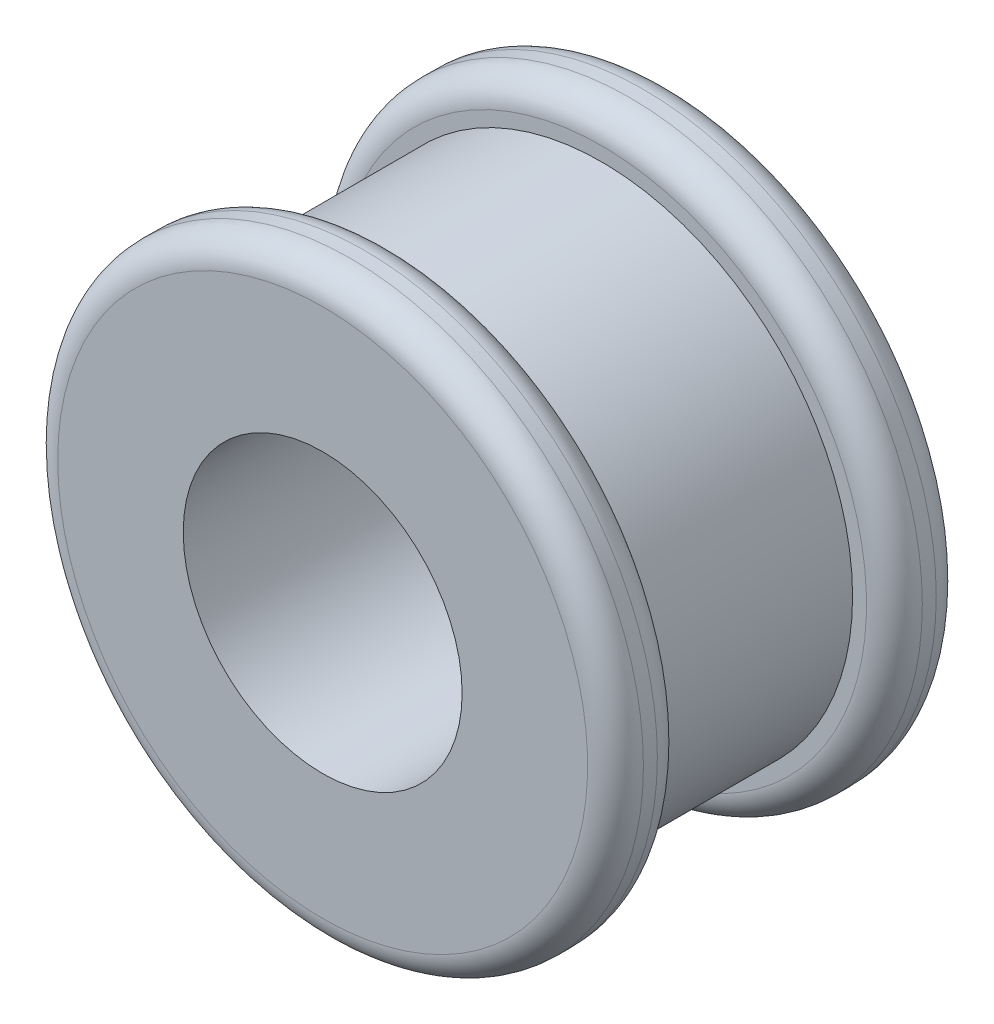
SolidWorks part; units mm, degrees
material "Teak"
ref_plane "Plano frontal" through (0, 0, 0) normal (0, 0, 1) x (1, 0, 0)
ref_plane "Plano superior" through (0, 0, 0) normal (0, 1, 0) x (1, 0, 0)
ref_plane "Plano direito" through (0, 0, 0) normal (1, 0, 0) x (0, 0, -1)
sketch "Sketch1" plane through (0, 0, 0) normal (1, 0, 0) x (0, 0, -1)
  line L0 (0, 0) -> (37.4107, 0) construction
  line L1 (0, 10) -> (25, 10)
  line L2 (25, 10) -> (25, 21)
  line L3 (25, 21) -> (20, 21)
  line L4 (20, 21) -> (20, 18)
  line L5 (20, 18) -> (5, 18)
  line L6 (5, 18) -> (5, 21)
  line L7 (5, 21) -> (0, 21)
  line L8 (0, 21) -> (0, 10)
  dimension "D1" = 5
  dimension "D2" = 15
  dimension "D3" = 21
  dimension "D4" = 3
  dimension "D6" = 10
revolve "Revolve1" add sketch "Sketch1" angle 360 about L0
fillet "Fillet1" radius 2 4 edges at (21, 0, -25) (21, 0, -20) (21, 0, -5) (21, 0, 0)
